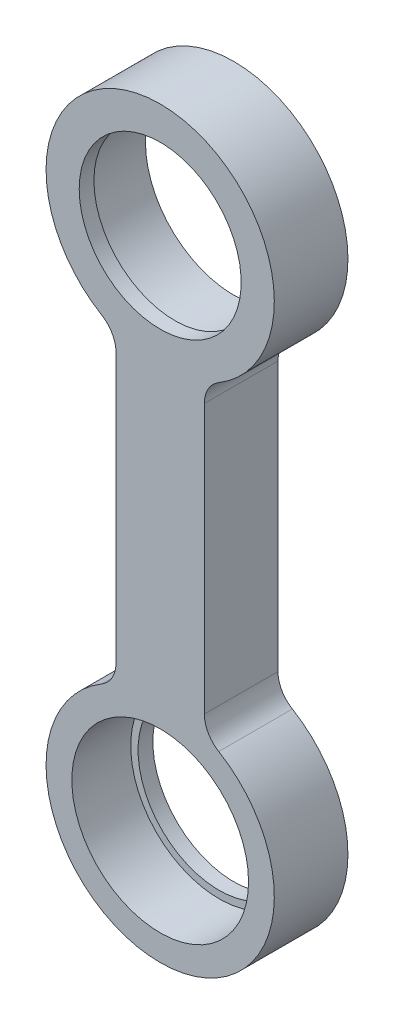
SolidWorks part; units mm, degrees
ref_plane "前视基准面" through (0, 0, 0) normal (0, 0, 1) x (1, 0, 0)
ref_plane "上视基准面" through (0, 0, 0) normal (0, 1, 0) x (1, 0, 0)
ref_plane "右视基准面" through (0, 0, 0) normal (1, 0, 0) x (0, 0, -1)
ref_plane "基准面1" through (0, 0, 0) normal (0, 0, -1) x (-1, 0, 0)
sketch "草图1" plane through (0, 0, 0) normal (0, 0, -1) x (-1, 0, 0)
  line L0 (-3, 27.8542) -> (-3, 7.1458)
  line L1 (3, 7.1458) -> (3, 27.8542)
  arc A0 (3, 27.8542) -> (-3, 27.8542) centre (0, 35) ccw
  arc A1 (-3, 7.1458) -> (3, 7.1458) centre (0, 0) ccw
extrude "凸台-拉伸1" add sketch "草图1" against normal blind 5
hole_wizard "M10 六角头螺栓的柱形沉头孔1" positions "草图3" profile "草图2" counterbore size "M10" standard "ANSI Metric"
sketch "草图3" plane through (0, 0, 0) normal (0, 0, -1) x (-1, 0, 0)
  point P0 (0, 35)
sketch "草图2" plane through (0, 35, 0) normal (1, 0, 0) x (0, 1, 0)
  line L0 (0, 0) -> (0, 5)
  line L1 (0, 5) -> (5.5, 5)
  line L3 (5.5, 5) -> (5.5, 4)
  line L4 (5.5, 4) -> (6, 4)
  line L5 (6, 4) -> (6, 0)
  line L7 (6, 0) -> (0, 0)
  line L11 (0, -6.35) -> (0, 107.95) construction
  dimension "通孔孔直径" = 11
  dimension "通孔孔深度" = 5
  dimension "柱形沉头孔直径" = 12
  dimension "柱形沉头孔深度" = 4
hole_wizard "M10 六角头螺栓的柱形沉头孔2" positions "草图5" profile "草图4" counterbore size "M10" standard "ANSI Metric"
sketch "草图5" plane through (0, 0, 5) normal (0, 0, 1) x (1, 0, 0)
  point P0 (0, 0)
sketch "草图4" plane through (0, 0, 5) normal (1, 0, 0) x (0, -1, 0)
  line L0 (0, 0) -> (0, 5)
  line L1 (0, 5) -> (5.5, 5)
  line L3 (5.5, 5) -> (5.5, 4)
  line L4 (5.5, 4) -> (6, 4)
  line L5 (6, 4) -> (6, 0)
  line L7 (6, 0) -> (0, 0)
  line L11 (0, -6.35) -> (0, 107.95) construction
  dimension "通孔孔直径" = 11
  dimension "通孔孔深度" = 5
  dimension "柱形沉头孔直径" = 12
  dimension "柱形沉头孔深度" = 4
fillet "圆角1" radius 2 4 edges at (-3, 27.8542, 2.5) (3, 27.8542, 2.5) (-3, 7.1458, 2.5) (3, 7.1458, 2.5)
